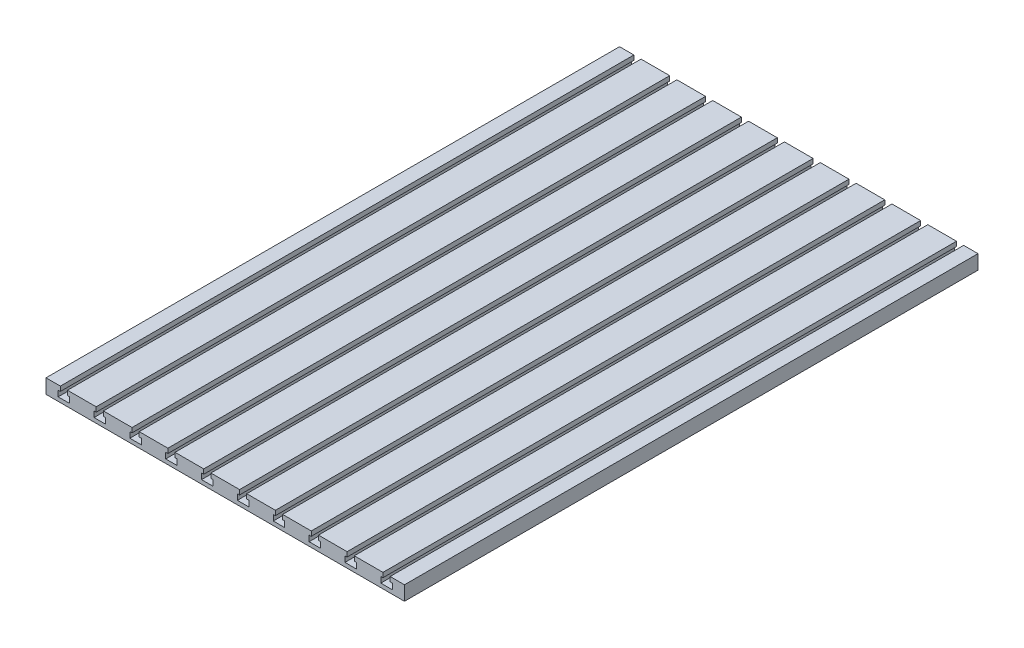
SolidWorks part; units mm, degrees
ref_plane "Front Plane" through (0, 0, 0) normal (0, 0, 1) x (1, 0, 0)
ref_plane "Top Plane" through (0, 0, 0) normal (0, 1, 0) x (1, 0, 0)
ref_plane "Right Plane" through (0, 0, 0) normal (1, 0, 0) x (0, 0, -1)
sketch "Sketch1" plane through (0, 0, 0) normal (0, 0, 1) x (1, 0, 0)
  line L1 (0, 0) -> (-500, 0)
  line L2 (0, 0) -> (0, 20)
  line L3 (0, 20) -> (-500, 20)
  line L4 (-500, 0) -> (-500, 20)
  dimension "D1" = 500
  dimension "D2" = 20
extrude "Boss-Extrude1" add sketch "Sketch1" along normal blind 800
sketch "Sketch2" plane through (0, 0, 800) normal (0, 0, 1) x (1, 0, 0)
  line L0 (-480, 20) -> (-480, 13.5)
  line L1 (0, 20) -> (-500, 20) construction
  line L2 (-480, 13.5) -> (-483, 13.5)
  line L3 (-483, 13.5) -> (-483, 5.5)
  line L4 (-483, 5.5) -> (-467, 5.5)
  line L5 (-475, 5.5) -> (-475, 20) construction
  line L6 (-467, 13.5) -> (-467, 5.5)
  line L7 (-470, 13.5) -> (-467, 13.5)
  line L8 (-470, 20) -> (-470, 13.5)
  line L9 (-430, 20) -> (-430, 13.5)
  line L10 (-430, 13.5) -> (-433, 13.5)
  line L11 (-433, 13.5) -> (-433, 5.5)
  line L12 (-433, 5.5) -> (-417, 5.5)
  line L13 (-417, 13.5) -> (-417, 5.5)
  line L14 (-420, 13.5) -> (-417, 13.5)
  line L15 (-420, 20) -> (-420, 13.5)
  line L16 (-430, 20) -> (-420, 20)
  line L17 (-425, 5.5) -> (-425, 20) construction
  line L18 (-380, 20) -> (-380, 13.5)
  line L19 (-380, 13.5) -> (-383, 13.5)
  line L20 (-383, 13.5) -> (-383, 5.5)
  line L21 (-383, 5.5) -> (-367, 5.5)
  line L22 (-367, 13.5) -> (-367, 5.5)
  line L23 (-370, 13.5) -> (-367, 13.5)
  line L24 (-370, 20) -> (-370, 13.5)
  line L25 (-380, 20) -> (-370, 20)
  line L26 (-375, 5.5) -> (-375, 20) construction
  line L27 (-330, 20) -> (-330, 13.5)
  line L28 (-330, 13.5) -> (-333, 13.5)
  line L29 (-333, 13.5) -> (-333, 5.5)
  line L30 (-333, 5.5) -> (-317, 5.5)
  line L31 (-317, 13.5) -> (-317, 5.5)
  line L32 (-320, 13.5) -> (-317, 13.5)
  line L33 (-320, 20) -> (-320, 13.5)
  line L34 (-330, 20) -> (-320, 20)
  line L35 (-325, 5.5) -> (-325, 20) construction
  line L36 (-280, 20) -> (-280, 13.5)
  line L37 (-280, 13.5) -> (-283, 13.5)
  line L38 (-283, 13.5) -> (-283, 5.5)
  line L39 (-283, 5.5) -> (-267, 5.5)
  line L40 (-267, 13.5) -> (-267, 5.5)
  line L41 (-270, 13.5) -> (-267, 13.5)
  line L42 (-270, 20) -> (-270, 13.5)
  line L43 (-280, 20) -> (-270, 20)
  line L44 (-275, 5.5) -> (-275, 20) construction
  line L45 (-230, 20) -> (-230, 13.5)
  line L46 (-230, 13.5) -> (-233, 13.5)
  line L47 (-233, 13.5) -> (-233, 5.5)
  line L48 (-233, 5.5) -> (-217, 5.5)
  line L49 (-217, 13.5) -> (-217, 5.5)
  line L50 (-220, 13.5) -> (-217, 13.5)
  line L51 (-220, 20) -> (-220, 13.5)
  line L52 (-230, 20) -> (-220, 20)
  line L53 (-225, 5.5) -> (-225, 20) construction
  line L54 (-180, 20) -> (-180, 13.5)
  line L55 (-180, 13.5) -> (-183, 13.5)
  line L56 (-183, 13.5) -> (-183, 5.5)
  line L57 (-183, 5.5) -> (-167, 5.5)
  line L58 (-167, 13.5) -> (-167, 5.5)
  line L59 (-170, 13.5) -> (-167, 13.5)
  line L60 (-170, 20) -> (-170, 13.5)
  line L61 (-180, 20) -> (-170, 20)
  line L62 (-175, 5.5) -> (-175, 20) construction
  line L63 (-130, 20) -> (-130, 13.5)
  line L64 (-130, 13.5) -> (-133, 13.5)
  line L65 (-133, 13.5) -> (-133, 5.5)
  line L66 (-133, 5.5) -> (-117, 5.5)
  line L67 (-117, 13.5) -> (-117, 5.5)
  line L68 (-120, 13.5) -> (-117, 13.5)
  line L69 (-120, 20) -> (-120, 13.5)
  line L70 (-130, 20) -> (-120, 20)
  line L71 (-125, 5.5) -> (-125, 20) construction
  line L72 (-80, 20) -> (-80, 13.5)
  line L73 (-80, 13.5) -> (-83, 13.5)
  line L74 (-83, 13.5) -> (-83, 5.5)
  line L75 (-83, 5.5) -> (-67, 5.5)
  line L76 (-67, 13.5) -> (-67, 5.5)
  line L77 (-70, 13.5) -> (-67, 13.5)
  line L78 (-70, 20) -> (-70, 13.5)
  line L79 (-80, 20) -> (-70, 20)
  line L80 (-75, 5.5) -> (-75, 20) construction
  line L81 (-500, 20) -> (-500, 0) construction
  line L82 (-480, 20) -> (-470, 20)
  line L83 (-30, 20) -> (-30, 13.5)
  line L84 (-30, 13.5) -> (-33, 13.5)
  line L85 (-33, 13.5) -> (-33, 5.5)
  line L86 (-33, 5.5) -> (-17, 5.5)
  line L87 (-17, 13.5) -> (-17, 5.5)
  line L88 (-20, 13.5) -> (-17, 13.5)
  line L89 (-20, 20) -> (-20, 13.5)
  line L90 (-30, 20) -> (-20, 20)
  line L91 (-25, 5.5) -> (-25, 20) construction
  dimension "D1" = 5
  dimension "D2" = 6.5
  dimension "D3" = 8
  dimension "D4" = 8
  dimension "D6" = 25
  dimension "D5" = 10
extrude "Cut-Extrude1" cut sketch "Sketch2" against normal through all
